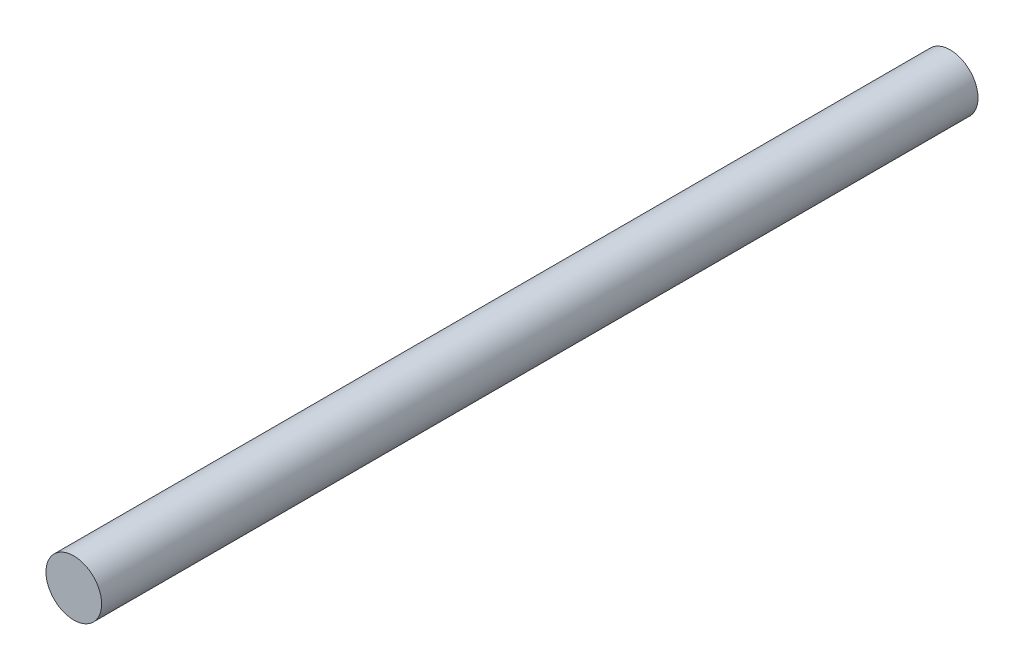
SolidWorks part; units mm, degrees
ref_plane "Front Plane" through (0, 0, 0) normal (0, 0, 1) x (1, 0, 0)
ref_plane "Top Plane" through (0, 0, 0) normal (0, 1, 0) x (1, 0, 0)
ref_plane "Right Plane" through (0, 0, 0) normal (1, 0, 0) x (0, 0, -1)
sketch "Sketch1" plane through (0, 0, 0) normal (0, 0, 1) x (1, 0, 0)
  circle A0 centre (0, 0) radius 2
extrude "Boss-Extrude2" add sketch "Sketch1" along normal blind 63
